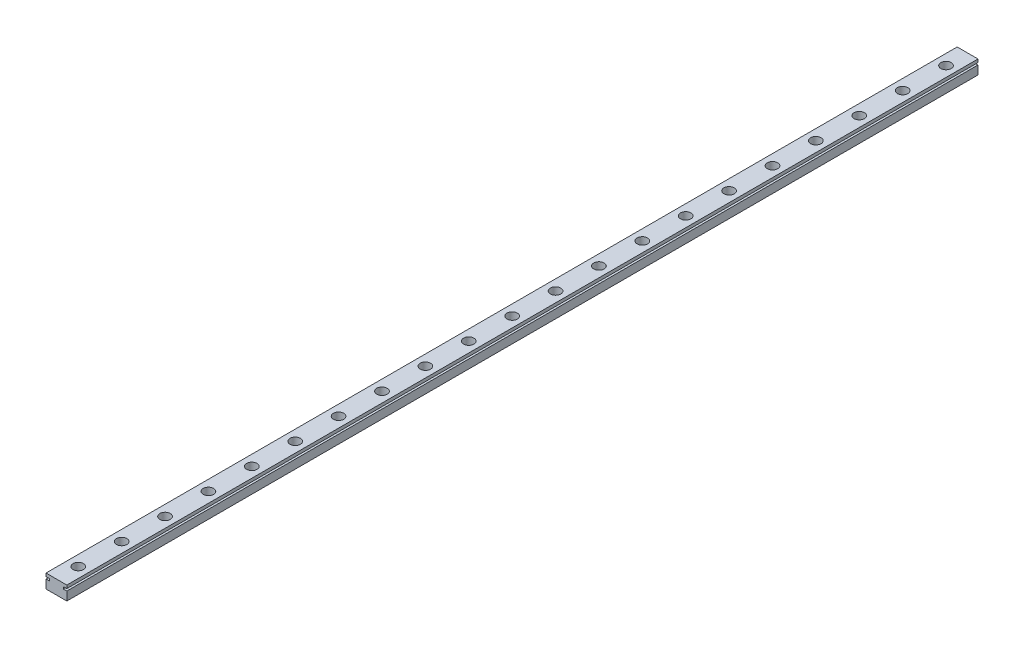
SolidWorks part; units mm, degrees
ref_plane "Plan de face" through (0, 0, 0) normal (0, 0, 1) x (1, 0, 0)
ref_plane "Plan de dessus" through (0, 0, 0) normal (0, 1, 0) x (1, 0, 0)
ref_plane "Plan de droite" through (0, 0, 0) normal (1, 0, 0) x (0, 0, -1)
sketch "Esquisse1" plane through (0, 0, 0) normal (0, 0, 1) x (1, 0, 0)
  line L0 (-2.288, -3.1489) -> (9.712, -3.1489)
  line L1 (9.712, -3.1489) -> (9.712, 1.8511)
  line L2 (9.712, 1.8511) -> (7.712, 1.8511)
  line L3 (7.712, 1.8511) -> (7.712, 3.0511)
  line L4 (7.712, 3.0511) -> (9.712, 3.0511)
  line L5 (9.712, 3.0511) -> (9.712, 4.8511)
  line L6 (9.712, 4.8511) -> (-2.288, 4.8511)
  line L7 (-2.288, 4.8511) -> (-2.288, 3.0511)
  line L8 (-2.288, 3.0511) -> (-0.288, 3.0511)
  line L9 (-0.288, 3.0511) -> (-0.288, 1.8511)
  line L10 (-0.288, 1.8511) -> (-2.288, 1.8511)
  line L11 (-2.288, 1.8511) -> (-2.288, -3.1489)
  dimension "D1" = 5
  dimension "D2" = 1.2
  dimension "D3" = 1.8
  dimension "D4" = 2
  dimension "D5" = 12
extrude "Boss.-Extru.1" add sketch "Esquisse1" along normal blind 525
sketch "Esquisse2" plane through (0, 4.8511, 0) normal (0, 1, 0) x (1, 0, 0)
  line L0 (9.712, -525) -> (-2.288, -525) construction
  circle A0 centre (3.7928, -512.5) radius 3
  circle A1 centre (3.7928, -487.5) radius 3
  circle A2 centre (3.7928, -462.5) radius 3
  circle A3 centre (3.7928, -437.5) radius 3
  circle A4 centre (3.7928, -412.5) radius 3
  circle A5 centre (3.7928, -387.5) radius 3
  circle A6 centre (3.7928, -362.5) radius 3
  circle A7 centre (3.7928, -337.5) radius 3
  circle A8 centre (3.7928, -312.5) radius 3
  circle A9 centre (3.7928, -287.5) radius 3
  circle A10 centre (3.7928, -262.5) radius 3
  circle A11 centre (3.7928, -237.5) radius 3
  circle A12 centre (3.7928, -212.5) radius 3
  circle A13 centre (3.7928, -187.5) radius 3
  circle A14 centre (3.7928, -162.5) radius 3
  circle A15 centre (3.7928, -137.5) radius 3
  circle A16 centre (3.7928, -112.5) radius 3
  circle A17 centre (3.7928, -87.5) radius 3
  circle A18 centre (3.7928, -62.5) radius 3
  circle A19 centre (3.7928, -37.5) radius 3
  circle A20 centre (3.7928, -12.5) radius 3
  circle A24 centre (3.7928, 62.5) radius 3 [skipped]
  circle A25 centre (3.7928, 37.5) radius 3 [skipped]
  circle A26 centre (3.7928, 12.5) radius 3 [skipped]
  dimension "D2" = 6
  dimension "D1" = 12.5
  dimension "D3" = 24
extrude "Enlèv. mat.-Extru.1" cut sketch "Esquisse2" against normal blind 4.5
sketch "Esquisse3" plane through (0, 0.3511, 0) normal (0, 1, 0) x (1, 0, 0)
  circle A0 centre (3.7928, -512.5) radius 1.75
  circle A1 centre (3.7928, -487.5) radius 1.75
  circle A2 centre (3.7928, -462.5) radius 1.75
  circle A3 centre (3.7928, -437.5) radius 1.75
  circle A4 centre (3.7928, -412.5) radius 1.75
  circle A5 centre (3.7928, -387.5) radius 1.75
  circle A6 centre (3.7928, -362.5) radius 1.75
  circle A7 centre (3.7928, -337.5) radius 1.75
  circle A8 centre (3.7928, -312.5) radius 1.75
  circle A9 centre (3.7928, -287.5) radius 1.75
  circle A10 centre (3.7928, -262.5) radius 1.75
  circle A11 centre (3.7928, -237.5) radius 1.75
  circle A12 centre (3.7928, -212.5) radius 1.75
  circle A13 centre (3.7928, -187.5) radius 1.75
  circle A14 centre (3.7928, -162.5) radius 1.75
  circle A15 centre (3.7928, -137.5) radius 1.75
  circle A16 centre (3.7928, -112.5) radius 1.75
  circle A17 centre (3.7928, -87.5) radius 1.75
  circle A18 centre (3.7928, -62.5) radius 1.75
  circle A19 centre (3.7928, -37.5) radius 1.75
  circle A20 centre (3.7928, -12.5) radius 1.75
  circle A24 centre (3.7928, 37.5) radius 1.75 [skipped]
  circle A25 centre (3.7928, 62.5) radius 1.75 [skipped]
  circle A26 centre (3.7928, 12.5) radius 1.75 [skipped]
  dimension "D1" = 3.5
  dimension "D2" = 24
extrude "Enlèv. mat.-Extru.2" cut sketch "Esquisse3" against normal up to next
sketch "Esquisse4" plane through (0, 0, 525) normal (0, 0, 1) x (1, 0, 0)
  line L0 (3.712, -3.1489) -> (3.712, 4.8511) construction
  line L1 (-2.288, -3.1489) -> (9.712, -3.1489) construction
  line L2 (9.712, 4.8511) -> (-2.288, 4.8511) construction
sketch "Esquisse5" plane through (0, 0, 0) normal (0, 0, -1) x (-1, 0, 0)
  line L0 (-3.712, 4.8511) -> (-3.712, -3.1489) construction
  line L1 (-9.712, 4.8511) -> (2.288, 4.8511) construction
  line L2 (2.288, -3.1489) -> (-9.712, -3.1489) construction
